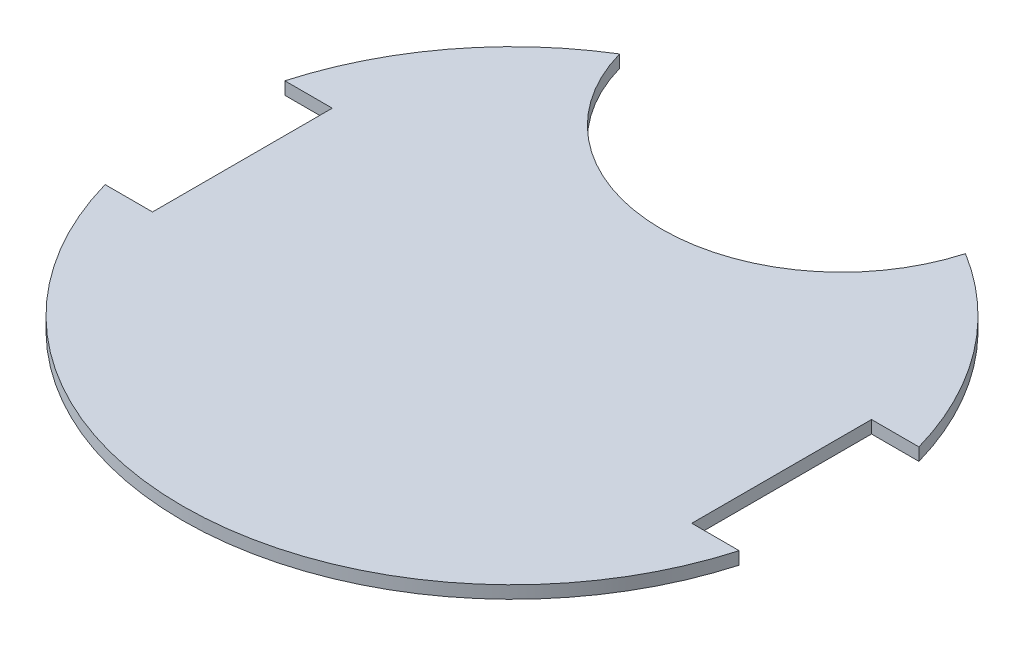
SolidWorks part; units mm, degrees
ref_plane "Front Plane" through (0, 0, 0) normal (0, 0, 1) x (1, 0, 0)
ref_plane "Top Plane" through (0, 0, 0) normal (0, 1, 0) x (1, 0, 0)
ref_plane "Right Plane" through (0, 0, 0) normal (1, 0, 0) x (0, 0, -1)
sketch "Sketch2" plane through (0, 0, 0) normal (0, 1, 0) x (1, 0, 0)
  line L1 (-139.7, 139.7) -> (139.7, 139.7)
  line L2 (-139.7, 139.7) -> (-139.7, -139.7)
  line L3 (-139.7, -139.7) -> (139.7, -139.7)
  line L4 (139.7, 139.7) -> (139.7, -139.7)
  line L5 (-139.7, 139.7) -> (139.7, -139.7) construction
  line L6 (-139.7, -139.7) -> (139.7, 139.7) construction
  point P0 (0, 0)
  dimension "D1" = 279.4
  dimension "D2" = 279.4
extrude "Boss-Extrude1" add sketch "Sketch2" along normal blind 5.334
sketch "Sketch3" plane through (0, 5.334, 0) normal (0, 1, 0) x (1, 0, 0)
  line L0 (-185.878, 0) -> (203.16, 0) construction
  line L1 (0, 161.3806) -> (0, -163.4252) construction
  arc A0 (-73.3114, 118.9182) -> (73.3114, 118.9182) centre (0, 0) ccw
  arc A1 (-73.3114, 118.9182) -> (73.3114, 118.9182) centre (0, 139.7) ccw
  dimension "D1" = 152.4
  dimension "D2" = 279.4
extrude "Cut-Extrude1" cut sketch "Sketch3" against normal through all flip side to cut
sketch "Sketch4" plane through (0, 5.334, 0) normal (0, 1, 0) x (1, 0, 0)
  line L0 (-187.5408, 0) -> (188.4178, 0) construction
  line L1 (0, 158.7873) -> (0, -160.4315) construction
  line L2 (-139.7, 0) -> (-139.7, 97.2286) construction
  line L3 (-139.7, 0) -> (-139.7, -79.7413) construction
  line L4 (165.1, -38.1) -> (114.3, 38.1) construction
  line L5 (-165.1, 38.1) -> (-114.3, 38.1)
  line L6 (-165.1, 38.1) -> (-165.1, -38.1)
  line L7 (-165.1, -38.1) -> (-114.3, -38.1)
  line L8 (-114.3, 38.1) -> (-114.3, -38.1)
  line L9 (-165.1, 38.1) -> (-114.3, -38.1) construction
  line L10 (-165.1, -38.1) -> (-114.3, 38.1) construction
  line L11 (165.1, 38.1) -> (114.3, -38.1) construction
  line L12 (114.3, 38.1) -> (114.3, -38.1)
  line L13 (165.1, -38.1) -> (114.3, -38.1)
  line L14 (165.1, 38.1) -> (165.1, -38.1)
  line L15 (165.1, 38.1) -> (114.3, 38.1)
  arc A0 (-73.3114, 118.9182) -> (73.3114, 118.9182) centre (0, 0) ccw construction
  dimension "D1" = 76.2
  dimension "D2" = 50.8
extrude "Cut-Extrude2" cut sketch "Sketch4" against normal through all
equation "\"width\"= .21"
equation "\"D1@Boss-Extrude1\" = \"width\""
